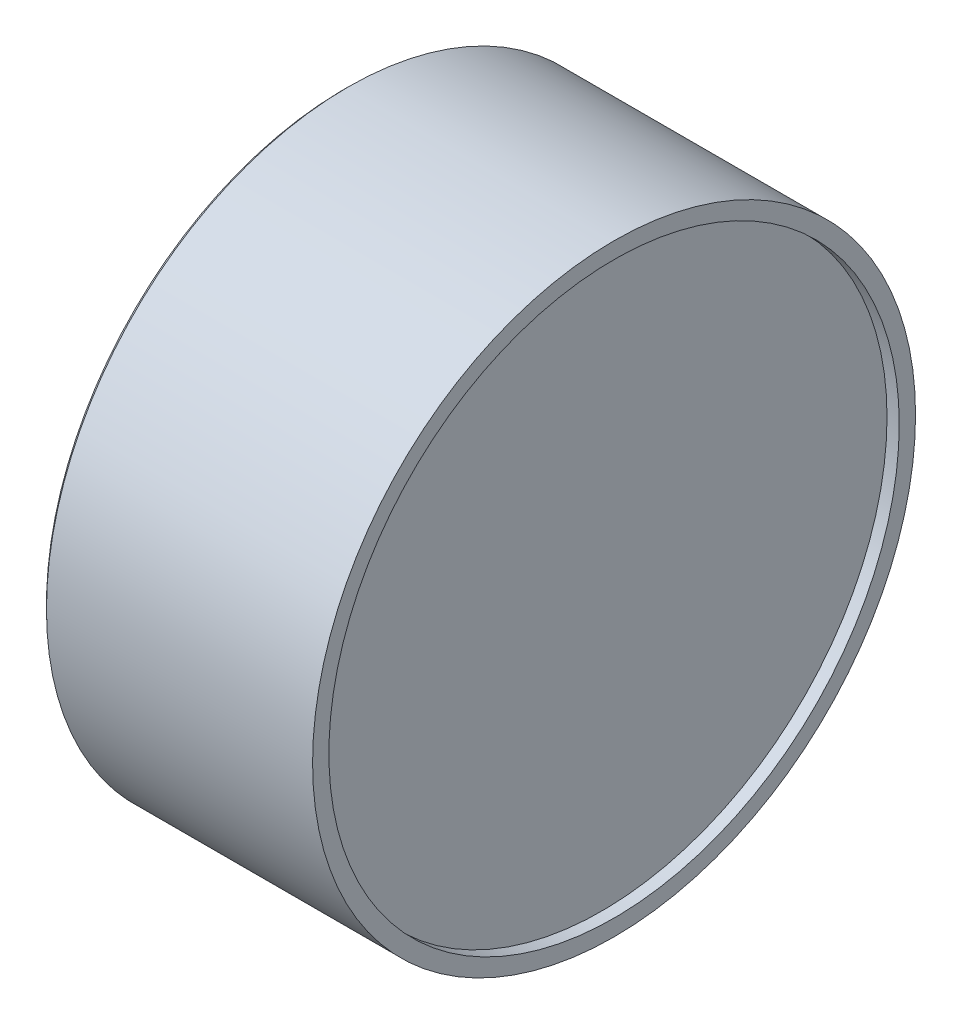
SolidWorks part; units mm, degrees
ref_plane "Front Plane" through (0, 0, 0) normal (0, 0, 1) x (1, 0, 0)
ref_plane "Top Plane" through (0, 0, 0) normal (0, 1, 0) x (1, 0, 0)
ref_plane "Right Plane" through (0, 0, 0) normal (1, 0, 0) x (0, 0, -1)
sketch "Sketch1" plane through (0, 0, 0) normal (1, 0, 0) x (0, 0, -1)
  circle A0 centre (0, 0) radius 37
  dimension "D1" = 74
extrude "Boss-Extrude1" add sketch "Sketch1" along normal mid plane 33.66
sketch "Sketch2" plane through (-16.83, 0, 0) normal (-1, 0, 0) x (0, 0, 1)
  line L0 (0, 0) -> (0, 31.5) construction
  circle A0 centre (0, 0) radius 31.5 construction
  circle A1 centre (0, 31.5) radius 1.25
  dimension "D1" = 63
  dimension "D2" = 2.5
extrude "Cut-Extrude1" cut sketch "Sketch2" against normal blind 6.7
chamfer "Chamfer1" distance 0.5 angle 45 1 edges at (-16.83, 31.5, 1.25)
pattern_circular "CirPattern1" count 6 over 360 about axis through (0, 0, 0) along (1, 0, 0) of "Cut-Extrude1", "Chamfer1"
sketch "Sketch3" plane through (-16.83, 0, 0) normal (-1, 0, 0) x (0, 0, 1)
  circle A0 centre (0, 0) radius 28
  dimension "D1" = 56
extrude "Cut-Extrude2" cut sketch "Sketch3" against normal blind 5.2
sketch "Sketch4" plane through (-11.63, 0, 0) normal (-1, 0, 0) x (0, 0, 1)
  line L1 (-15.5, -15.5) -> (15.5, -15.5) construction
  line L2 (-15.5, -15.5) -> (-15.5, 15.5) construction
  line L3 (-15.5, 15.5) -> (15.5, 15.5) construction
  line L4 (15.5, -15.5) -> (15.5, 15.5) construction
  line L5 (-15.5, -15.5) -> (15.5, 15.5) construction
  line L6 (-15.5, 15.5) -> (15.5, -15.5) construction
  circle A0 centre (15.5, 15.5) radius 3.5
  circle A1 centre (-15.5, 15.5) radius 3.5
  circle A2 centre (-15.5, -15.5) radius 3.5
  circle A3 centre (15.5, -15.5) radius 3.5
  point P0 (0, 0)
  dimension "D2" = 7
  dimension "D1" = 31
extrude "Boss-Extrude2" add sketch "Sketch4" along normal blind 3.65
sketch "Sketch5" plane through (-15.28, 0, 0) normal (-1, 0, 0) x (0, 0, 1)
  circle A0 centre (-15.5, 15.5) radius 1.25
  circle A1 centre (15.5, 15.5) radius 1.25
  circle A2 centre (15.5, -15.5) radius 1.25
  circle A3 centre (-15.5, -15.5) radius 1.25
  dimension "D1" = 2.5
extrude "Cut-Extrude3" cut sketch "Sketch5" against normal blind 5.15
chamfer "Chamfer2" distance 0.5 angle 45 2 edges at (-16.83, 0, 28) (-16.83, 0, -37)
chamfer "Chamfer3" distance 0.5 angle 45 4 edges at (-15.28, 15.5, 16.75) (-15.28, -15.5, 16.75) (-15.28, -15.5, -14.25) (-15.28, 15.5, -14.25)
sketch "Sketch6" plane through (16.83, 0, 0) normal (1, 0, 0) x (0, 0, -1)
  circle A0 centre (0, 0) radius 35
  circle A1 centre (0, 0) radius 37 construction
  dimension "D1" = 2
extrude "Cut-Extrude4" cut sketch "Sketch6" against normal blind 2
sketch "Sketch7" plane through (16.83, 0, 0) normal (1, 0, 0) x (0, 0, -1)
  circle A0 centre (0, 0) radius 35 construction
  circle A1 centre (0, 0) radius 37
  circle A2 centre (0, 0) radius 37
  circle A3 centre (0, 0) radius 35
  dimension "D1" = 0
extrude "Cut-Extrude5" cut sketch "Sketch7" against normal blind 0.5
